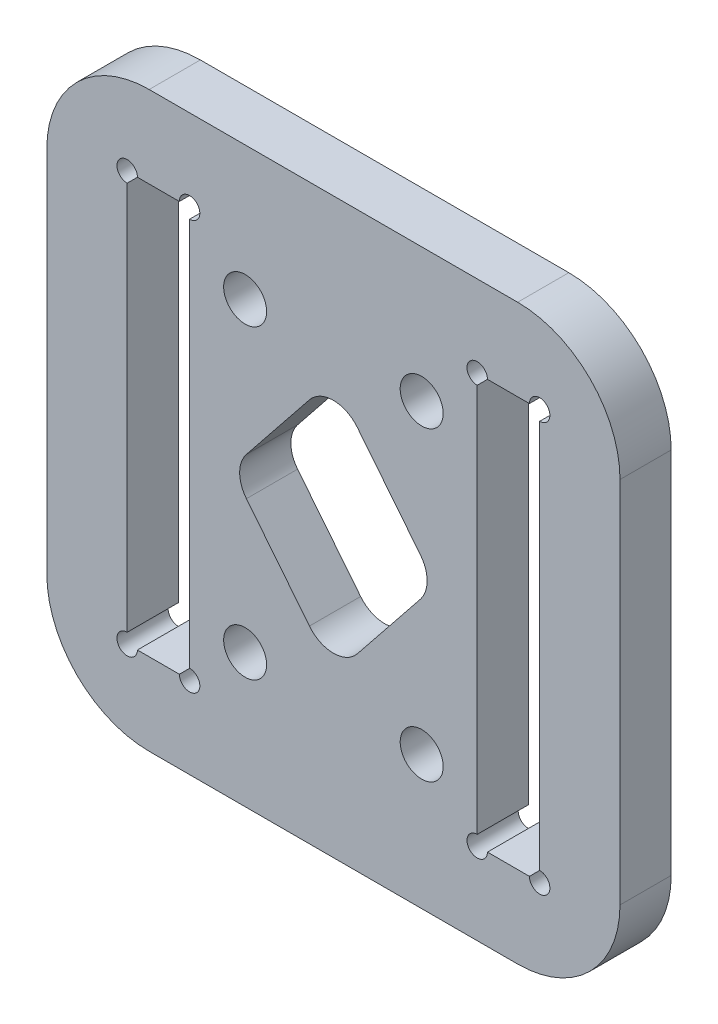
SolidWorks part; units mm, degrees
ref_plane "前视基准面" through (0, 0, 0) normal (0, 0, 1) x (1, 0, 0)
ref_plane "上视基准面" through (0, 0, 0) normal (0, 1, 0) x (1, 0, 0)
ref_plane "右视基准面" through (0, 0, 0) normal (1, 0, 0) x (0, 0, -1)
other "Configuration Table"
sketch "草图1" plane through (0, 0, 0) normal (0, 0, 1) x (1, 0, 0)
  line L0 (0, -28) -> (56, -28) construction
  line L5 (0, 0) -> (56, 0)
  line L6 (0, 0) -> (0, -56)
  line L7 (0, -56) -> (56, -56)
  line L8 (56, 0) -> (56, -56)
  line L9 (28, 0) -> (28, -56) construction
  circle A0 centre (28, -28) radius 17.25 construction
  circle A1 centre (36.625, -13.0611) radius 2.1
  circle A2 centre (19.375, -13.0611) radius 2.1
  circle A3 centre (36.625, -42.9389) radius 2.1
  circle A4 centre (19.375, -42.9389) radius 2.1
  dimension "D3" = 34.5
  dimension "D4" = 60
  dimension "D5" = 4.2
  dimension "D1" = 56
  dimension "D2" = 56
extrude "凸台-拉伸1" add sketch "草图1" along normal blind 5
fillet "圆角1" radius 10 4 edges at (56, -56, 2.5) (0, -56, 2.5) (0, 0, 2.5) (56, 0, 2.5)
sketch "草图2" plane through (0, 0, 5) normal (0, 0, 1) x (1, 0, 0)
  line L0 (28, 0) -> (28, -56) construction
  line L1 (56, 0) -> (0, 0) construction
  line L2 (0, -56) -> (56, -56) construction
  line L3 (13.95, 0) -> (13.95, -56)
  line L4 (42.05, 0) -> (42.05, -56)
  line L5 (7.85, -8) -> (13.95, -8)
  line L6 (7.85, -8) -> (7.85, -48)
  line L7 (48.15, -8) -> (48.15, -48)
  line L8 (7.85, -48) -> (13.95, -48)
  line L9 (0, -28) -> (56, -28) construction
  line L10 (48.15, -48) -> (42.05, -48)
  line L11 (0, -56) -> (56, -56)
  line L12 (56, -56) -> (56, 0)
  line L13 (56, 0) -> (0, 0)
  line L14 (0, 0) -> (0, -56)
  line L15 (0, -56) -> (56, -56)
  line L16 (56, -56) -> (56, 0)
  line L17 (56, 0) -> (0, 0)
  line L18 (0, 0) -> (0, -56)
  line L19 (48.15, -8) -> (42.05, -8)
  circle A0 centre (13.95, -8) radius 1
  circle A1 centre (7.85, -8) radius 1
  circle A2 centre (7.85, -48) radius 1
  circle A3 centre (13.95, -48) radius 1
  circle A12 centre (42.05, -8) radius 1
  circle A13 centre (42.05, -48) radius 1
  circle A14 centre (48.15, -48) radius 1
  circle A15 centre (48.15, -8) radius 1
  dimension "D5" = 2
  dimension "D6" = 2
  dimension "D7" = 2
  dimension "D8" = 2
  dimension "D1" = 28.1
  dimension "D2" = 0
  dimension "D3" = 6.1
  dimension "D4" = 8
extrude "切除-拉伸1" cut sketch "草图2" against normal blind 16 contours L7 A15 L19 A12 L4 A13 L10 A14 | A12 L4 L19 | A12 L19 L4 | A12 L4 | A15 L19 L7 | A15 L7 L19 | A14 L10 L7 | A14 L7 L10 | A13 L4 L10 | A13 L10 L4 | A13 L4 | L3 A3 L8 | L8 A3 L3 | L3 A3 | A3 L3 A0 L5 A1 L6 A2 L8 | L6 A2 L8 | L8 A2 L6 | L5 A1 L6 | L6 A1 L5 | L3 A0 | L3 A0 L5 | L5 A0 L3
sketch "草图3" plane through (0, 0, 5) normal (0, 0, 1) x (1, 0, 0)
  line L4 (0, -28) -> (56, -28) construction
  line L5 (28, 0) -> (28, -56) construction
  line L6 (25.6574, -18.4283) -> (19.4993, -26.1259)
  line L7 (19.4993, -29.8741) -> (25.6574, -37.5717)
  line L8 (0, -56) -> (56, -56)
  line L9 (56, -56) -> (56, 0)
  line L10 (56, 0) -> (0, 0)
  line L11 (0, 0) -> (0, -56)
  line L12 (0, -56) -> (56, -56)
  line L13 (56, -56) -> (56, 0)
  line L14 (56, 0) -> (0, 0)
  line L15 (0, 0) -> (0, -56)
  line L17 (36.5007, -29.8741) -> (30.3426, -37.5717)
  line L18 (30.3426, -18.4283) -> (36.5007, -26.1259)
  arc A4 (36.5007, -29.8741) -> (36.5007, -26.1259) centre (34.1581, -28) ccw
  arc A5 (25.6574, -37.5717) -> (30.3426, -37.5717) centre (28, -35.6977) ccw
  arc A6 (19.4993, -26.1259) -> (19.4993, -29.8741) centre (21.8419, -28) ccw
  arc A7 (25.6574, -18.4283) -> (30.3426, -18.4283) centre (28, -20.3023) cw
  point P11 (28, -28)
  point P17 (38, -28)
  point P25 (28, -40.5)
  point P30 (18, -28)
  point P33 (28, -15.5)
  dimension "D4" = 3
  dimension "D2" = 25
  dimension "D3" = 10
  dimension "D5" = 56
  dimension "D1" = 0
extrude "切除-拉伸2" cut sketch "草图3" against normal blind 16 contours L18 A4 L17 A5 L7 A6 L6 A7
